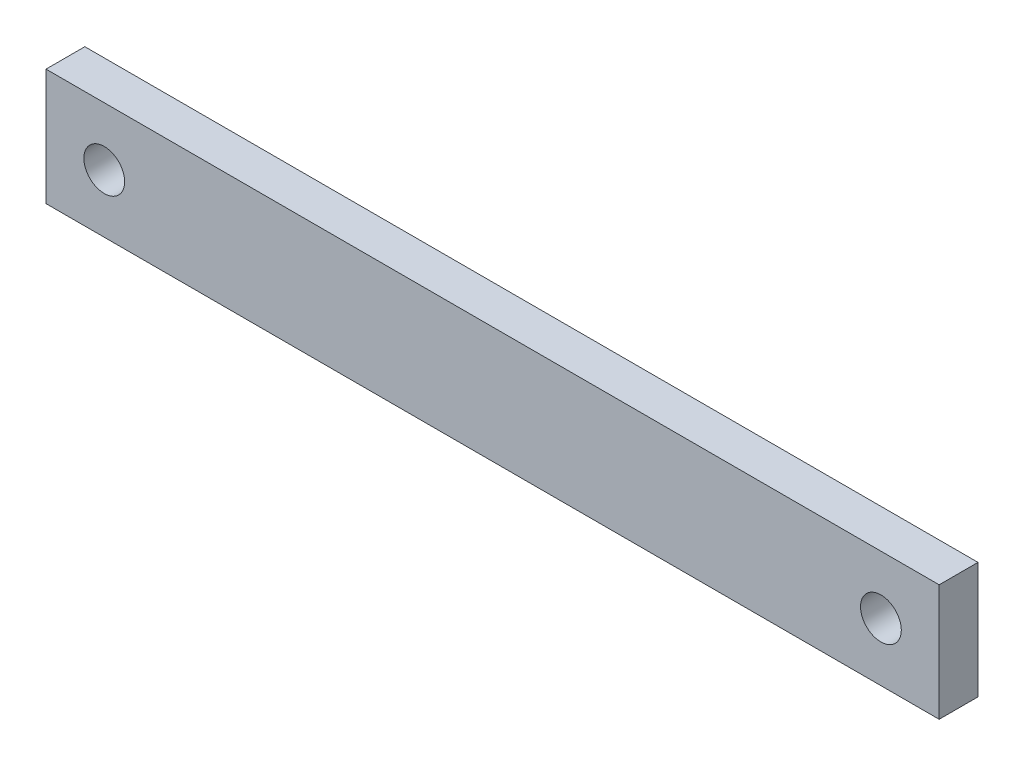
SolidWorks part; units mm, degrees
material "7075-T6 (SN)"
ref_plane "Front Plane" through (0, 0, 0) normal (0, 0, 1) x (1, 0, 0)
ref_plane "Top Plane" through (0, 0, 0) normal (0, 1, 0) x (1, 0, 0)
ref_plane "Right Plane" through (0, 0, 0) normal (1, 0, 0) x (0, 0, -1)
sketch "Sketch1" plane through (0, 0, 0) normal (0, 0, 1) x (1, 0, 0)
  line L1 (-3, -3) -> (43, -3)
  line L2 (-3, -3) -> (-3, 3)
  line L3 (-3, 3) -> (43, 3)
  line L4 (43, -3) -> (43, 3)
  circle A0 centre (0, 0) radius 1.05
  circle A1 centre (40, 0) radius 1.05
extrude "L40_Link" add sketch "Sketch1" along normal blind 2
